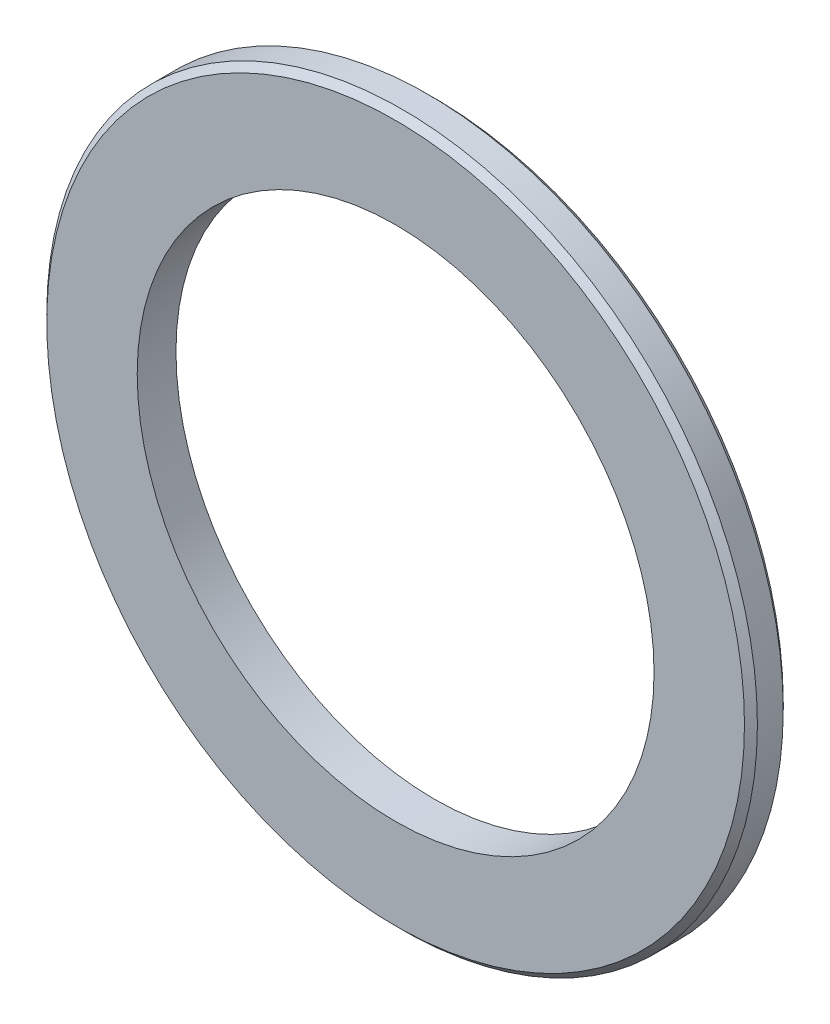
SolidWorks part; units mm, degrees
material "AISI 304"
ref_plane "Спереди" through (0, 0, 0) normal (0, 0, 1) x (1, 0, 0)
ref_plane "Сверху" through (0, 0, 0) normal (0, 1, 0) x (1, 0, 0)
ref_plane "Справа" through (0, 0, 0) normal (1, 0, 0) x (0, 0, -1)
sketch "Эскиз1" plane through (0, 0, 0) normal (0, 0, 1) x (1, 0, 0)
  circle A0 centre (0, 0) radius 27.5
  circle A1 centre (0, 0) radius 20
  dimension "D1" = 55
  dimension "65" = 40
extrude "Бобышка-Вытянуть1" add sketch "Эскиз1" along normal blind 3
chamfer "Фаска1" distance 0.5 angle 45 2 edges at (27.5, 0, 0) (27.5, 0, 3)
